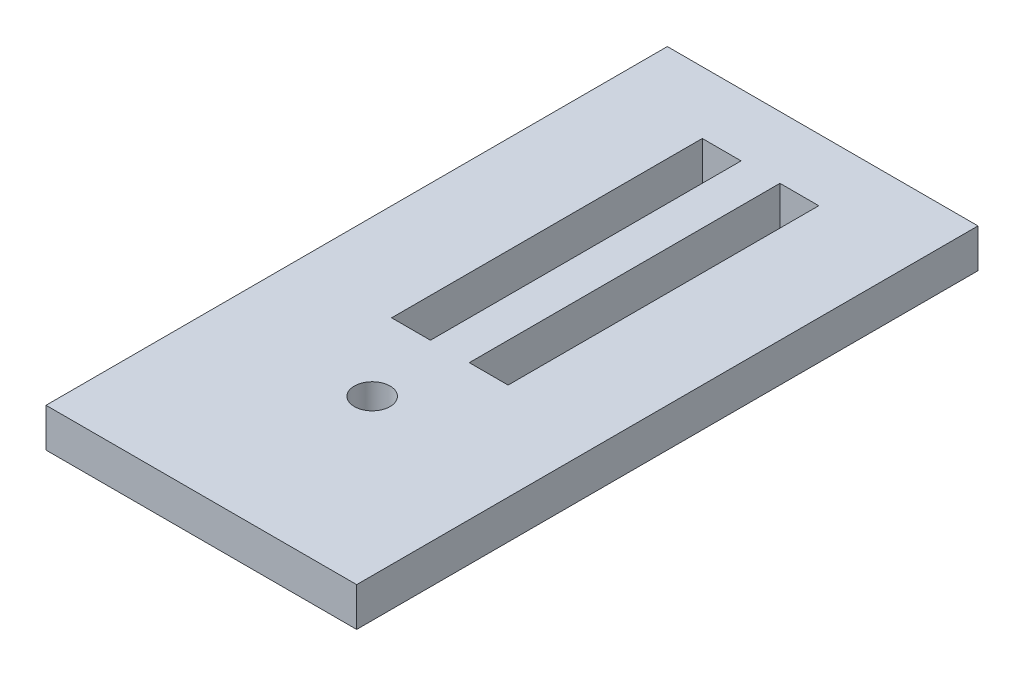
SolidWorks part; units mm, degrees
ref_plane "Front Plane" through (0, 0, 0) normal (0, 0, 1) x (1, 0, 0)
ref_plane "Top Plane" through (0, 0, 0) normal (0, 1, 0) x (1, 0, 0)
ref_plane "Right Plane" through (0, 0, 0) normal (1, 0, 0) x (0, 0, -1)
sketch "Sketch1" plane through (0, 0, 0) normal (0, 1, 0) x (1, 0, 0)
  line L0 (11.1125, 20.32) -> (7.9375, 20.32)
  line L1 (0, 0) -> (25.4, 0)
  line L2 (0, 0) -> (0, 50.8)
  line L3 (0, 50.8) -> (25.4, 50.8)
  line L4 (25.4, 0) -> (25.4, 50.8)
  line L5 (12.7, 50.8) -> (12.7, 0) construction
  line L6 (7.9375, 45.72) -> (7.9375, 20.32)
  line L10 (14.2875, 45.72) -> (14.2875, 20.32)
  line L11 (11.1125, 45.72) -> (7.9375, 45.72)
  line L12 (11.1125, 45.72) -> (11.1125, 20.32)
  line L13 (14.2875, 45.72) -> (17.4625, 45.72)
  line L15 (14.2875, 20.32) -> (17.4625, 20.32)
  line L16 (17.4625, 45.72) -> (17.4625, 20.32)
  circle A0 centre (12.7, 13.97) radius 1.4605
  point P7 (12.7, 33.02)
  dimension "D5" = 2.921
  dimension "D1" = 50.8
  dimension "D2" = 25.4
  dimension "D6" = 3.175
  dimension "D7" = 25.4
  dimension "D8" = 6.35
extrude "Boss-Extrude1" add sketch "Sketch1" along normal blind 3.175
